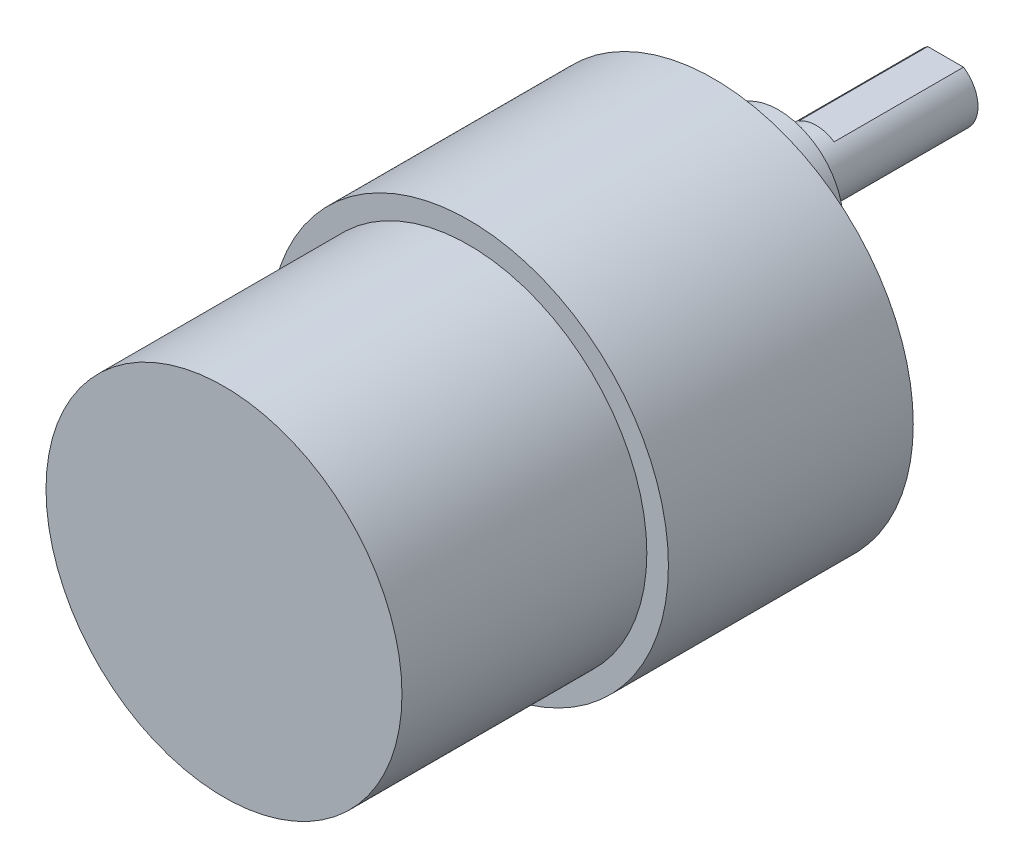
SolidWorks part; units mm, degrees
ref_plane "前视基准面" through (0, 0, 0) normal (0, 0, 1) x (1, 0, 0)
ref_plane "上视基准面" through (0, 0, 0) normal (0, 1, 0) x (1, 0, 0)
ref_plane "右视基准面" through (0, 0, 0) normal (1, 0, 0) x (0, 0, -1)
sketch "草图1" plane through (0, 0, 0) normal (0, 0, 1) x (1, 0, 0)
  circle A0 centre (0, 0) radius 18.5
  dimension "D1" = 37
extrude "凸台-拉伸1" add sketch "草图1" along normal blind 22.7
sketch "草图2" plane through (0, 0, 22.7) normal (0, 0, 1) x (1, 0, 0)
  circle A0 centre (0, 0) radius 16.5
  dimension "D1" = 33
extrude "凸台-拉伸2" add sketch "草图2" along normal blind 22.7
sketch "草图3" plane through (0, 0, 0) normal (0, 0, -1) x (-1, 0, 0)
  line L0 (0, 0) -> (0, 18.5) construction
  circle A0 centre (0, 7) radius 6
  circle A1 centre (0, 0) radius 7 construction
  circle A2 centre (0, 0) radius 18.5 construction
  dimension "D1" = 14
  dimension "D2" = 12
extrude "凸台-拉伸3" add sketch "草图3" along normal blind 6
sketch "草图4" plane through (0, 0, -6) normal (0, 0, -1) x (-1, 0, 0)
  circle A0 centre (0, 7) radius 3
  dimension "D1" = 6
extrude "凸台-拉伸4" add sketch "草图4" along normal blind 15.5
sketch "草图5" plane through (0, 0, -21.5) normal (0, 0, -1) x (-1, 0, 0)
  line L1 (-6.2371, 13.1429) -> (8.1137, 13.1429)
  line L2 (-6.2371, 13.1429) -> (-6.2371, 9.5)
  line L3 (-6.2371, 9.5) -> (8.1137, 9.5)
  line L4 (8.1137, 13.1429) -> (8.1137, 9.5)
  circle A0 centre (0, 7) radius 3 construction
  dimension "D1" = 2.5
extrude "切除-拉伸1" cut sketch "草图5" against normal blind 12
sketch "草图6" plane through (0, 0, 0) normal (0, 0, -1) x (-1, 0, 0)
  circle A0 centre (0, 0) radius 15.5 construction
  circle A1 centre (0, 15.5) radius 1.6
  circle A2 centre (13.4234, 7.75) radius 1.6
  circle A3 centre (13.4234, -7.75) radius 1.6
  circle A4 centre (0, -15.5) radius 1.6
  circle A5 centre (-13.4234, -7.75) radius 1.6
  circle A6 centre (-13.4234, 7.75) radius 1.6
  point P18 (0, 0)
  dimension "D1" = 31
  dimension "D2" = 3.2
  dimension "D3" = 6
extrude "切除-拉伸2" cut sketch "草图6" against normal blind 10
